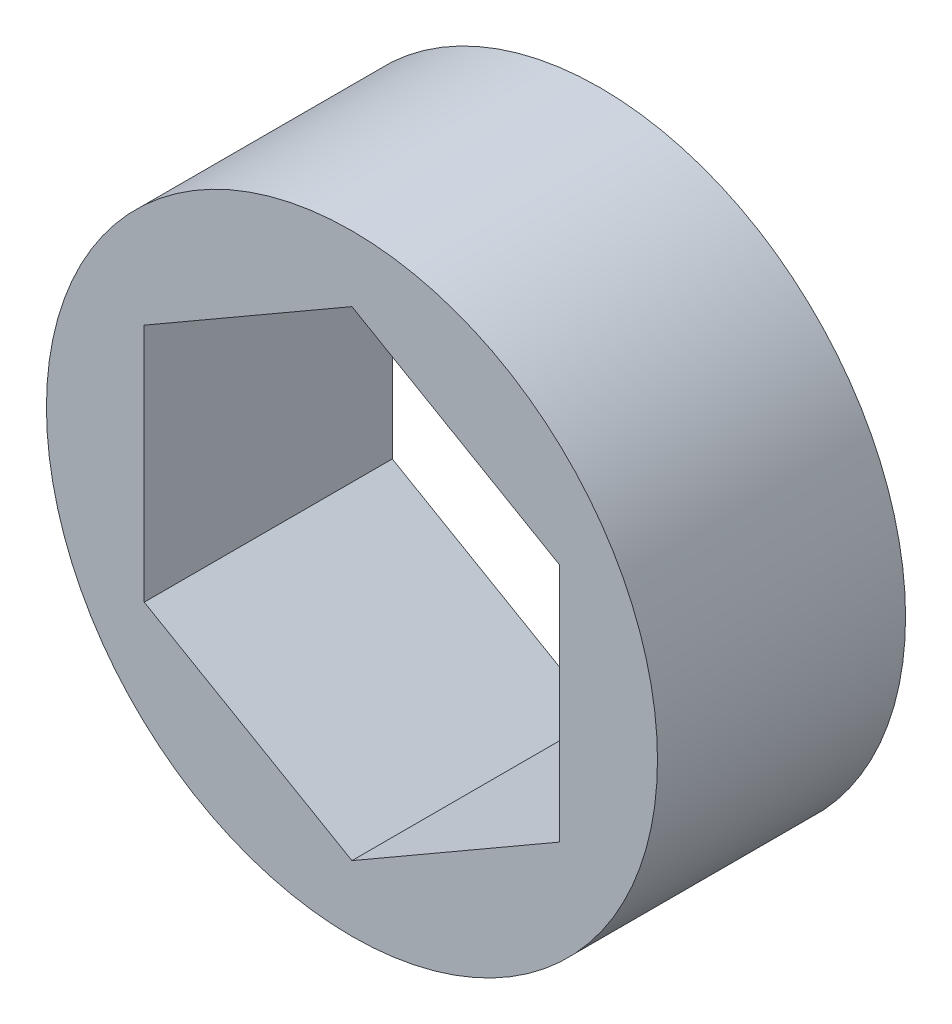
SolidWorks part; units mm, degrees
material "PET"
ref_plane "Front Plane" through (0, 0, 0) normal (0, 0, 1) x (1, 0, 0)
ref_plane "Top Plane" through (0, 0, 0) normal (0, 1, 0) x (1, 0, 0)
ref_plane "Right Plane" through (0, 0, 0) normal (1, 0, 0) x (0, 0, -1)
sketch "Sketch1" plane through (0, 0, 0) normal (0, 0, 1) x (1, 0, 0)
  line L1 (0, 7.479) -> (-6.477, 3.7395)
  line L2 (-6.477, 3.7395) -> (-6.477, -3.7395)
  line L3 (-6.477, -3.7395) -> (0, -7.479)
  line L4 (0, -7.479) -> (6.477, -3.7395)
  line L5 (6.477, -3.7395) -> (6.477, 3.7395)
  line L6 (6.477, 3.7395) -> (0, 7.479)
  circle A0 centre (0, 0) radius 9.525
  circle A1 centre (0, 0) radius 6.477 construction
  dimension "D1" = 12.954
  dimension "D2" = 19.05
extrude "Boss-Extrude1" add sketch "Sketch1" along normal blind 7.7343
